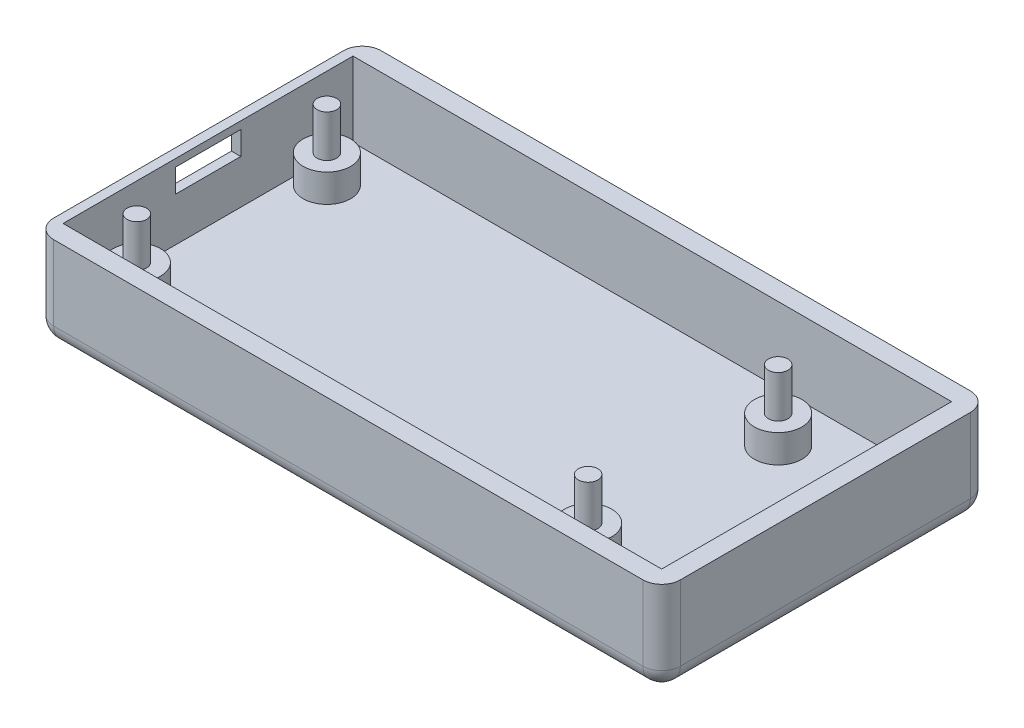
SolidWorks part; units mm, degrees
ref_plane "Alzado" through (0, 0, 0) normal (0, 0, 1) x (1, 0, 0)
ref_plane "Planta" through (0, 0, 0) normal (0, 1, 0) x (1, 0, 0)
ref_plane "Vista lateral" through (0, 0, 0) normal (1, 0, 0) x (0, 0, -1)
sketch "Croquis1" plane through (0, 0, 0) normal (0, 1, 0) x (1, 0, 0)
  line L1 (0, 0) -> (67, 0)
  line L2 (0, 0) -> (0, 35)
  line L3 (0, 35) -> (67, 35)
  line L4 (67, 0) -> (67, 35)
  dimension "D1" = 67
  dimension "D2" = 35
extrude "Saliente-Extruir1" add sketch "Croquis1" along normal blind 10
sketch "Croquis2" plane through (0, 10, 0) normal (0, 1, 0) x (1, 0, 0)
  line L0 (2, 2) -> (1, 2)
  line L1 (1, 2) -> (1, 33)
  line L2 (1, 33) -> (2, 33)
  line L8 (2, 33) -> (2, 2)
  line L9 (2, 2) -> (65, 2)
  line L10 (65, 2) -> (65, 33)
  line L11 (65, 33) -> (2, 33)
  line L13 (2, 2) -> (65, 2)
  line L14 (65, 2) -> (65, 33)
  line L15 (65, 33) -> (2, 33)
  dimension "D2" = 1
  dimension "D1" = 2
extrude "Cortar-Extruir1" cut sketch "Croquis2" against normal blind 8
sketch "Croquis3" plane through (0, 2, 0) normal (0, 1, 0) x (1, 0, 0)
  line L0 (1, 33) -> (1, 2) construction
  line L1 (1, 30.2) -> (54.34, 30.2) construction
  line L2 (1, 30.2) -> (1, 4.8) construction
  line L3 (1, 4.8) -> (54.34, 4.8) construction
  line L4 (54.34, 30.2) -> (54.34, 4.8) construction
  line L5 (0, 17.5) -> (67, 17.5) construction
  line L6 (0, 35) -> (0, 0) construction
  line L7 (67, 0) -> (67, 35) construction
  line L8 (1, 27.66) -> (54.34, 27.66) construction
  line L9 (3.55, 17.5) -> (3.55, 30.2) construction
  line L10 (51.8, 17.5) -> (51.8, 30.2) construction
  line L15 (1, 33) -> (1, 2) construction
  line L16 (1, 33) -> (1, 2) construction
  circle A0 centre (3.55, 27.66) radius 2.54
  circle A1 centre (51.8, 27.66) radius 2.54
  circle A2 centre (3.55, 7.34) radius 2.54
  circle A3 centre (51.8, 7.34) radius 2.54
  point P12 (54.34, 17.5)
  dimension "D1" = 53.34
  dimension "D2" = 25.4
  dimension "D3" = 10.16
  dimension "D4" = 2.55
  dimension "D5" = 2.54
extrude "Saliente-Extruir2" add sketch "Croquis3" along normal blind 3 contours A1 | A3 | A2 | A0
sketch "Croquis4" plane through (0, 5, 0) normal (0, 1, 0) x (1, 0, 0)
  circle A12 centre (3.55, 7.34) radius 2.54 construction
  circle A13 centre (51.8, 7.34) radius 2.54 construction
  circle A14 centre (51.8, 27.66) radius 2.54 construction
  circle A15 centre (3.55, 27.66) radius 2.54 construction
  circle A16 centre (3.55, 7.34) radius 2.54 construction
  circle A17 centre (51.8, 7.34) radius 2.54 construction
  circle A18 centre (51.8, 27.66) radius 2.54 construction
  circle A19 centre (3.55, 27.66) radius 2.54 construction
  circle A20 centre (3.55, 7.34) radius 1.04
  circle A21 centre (51.8, 7.34) radius 1.04
  circle A22 centre (51.8, 27.66) radius 1.04
  circle A23 centre (3.55, 27.66) radius 1.04
  dimension "D1" = 1.5
extrude "Saliente-Extruir3" add sketch "Croquis4" along normal blind 4.5
sketch "Croquis6" plane through (0, 0, 0) normal (-1, 0, 0) x (0, 0, 1)
  line L0 (-4.8, 5) -> (-9.88, 5) construction
  line L1 (-4.8, 5) -> (-9.88, 5) construction
  line L2 (-9.88, 5) -> (-35, 5) construction
  line L4 (-17.5, 10) -> (-17.5, 0) construction
  line L5 (-35, 10) -> (0, 10) construction
  line L6 (-35, 0) -> (0, 0) construction
  line L7 (-35, 10) -> (-35, 0) construction
  line L13 (-14, 6.7) -> (-21, 6.7)
  line L14 (-14, 6.7) -> (-14, 9.2)
  line L15 (-14, 9.2) -> (-21, 9.2)
  line L16 (-21, 6.7) -> (-21, 9.2)
  point P3 (-17.5, 9.2)
  dimension "D1" = 7
  dimension "D2" = 2.5
  dimension "D3" = 1.7
extrude "Cortar-Extruir2" cut sketch "Croquis6" against normal blind 3
fillet "Redondeo1" radius 2 8 edges at (33.5, 0, -35) (0, 5, -35) (67, 5, -35) (67, 0, -17.5) (67, 5, 0) (33.5, 0, 0) (0, 0, -17.5) (0, 5, 0)
sketch "Croquis7" plane through (0, 0, 0) normal (0, -1, 0) x (1, 0, 0)
  line L0 (2, -20.8441) -> (65, -20.8441) construction
  line L1 (2, -2) -> (2, -33) construction
  line L2 (65, -33) -> (65, -2) construction
  text T0 "<b>gVIE</b>" font "Century Gothic" height 9
extrude "Cortar-Extruir3" cut sketch "Croquis7" against normal blind 0.8
